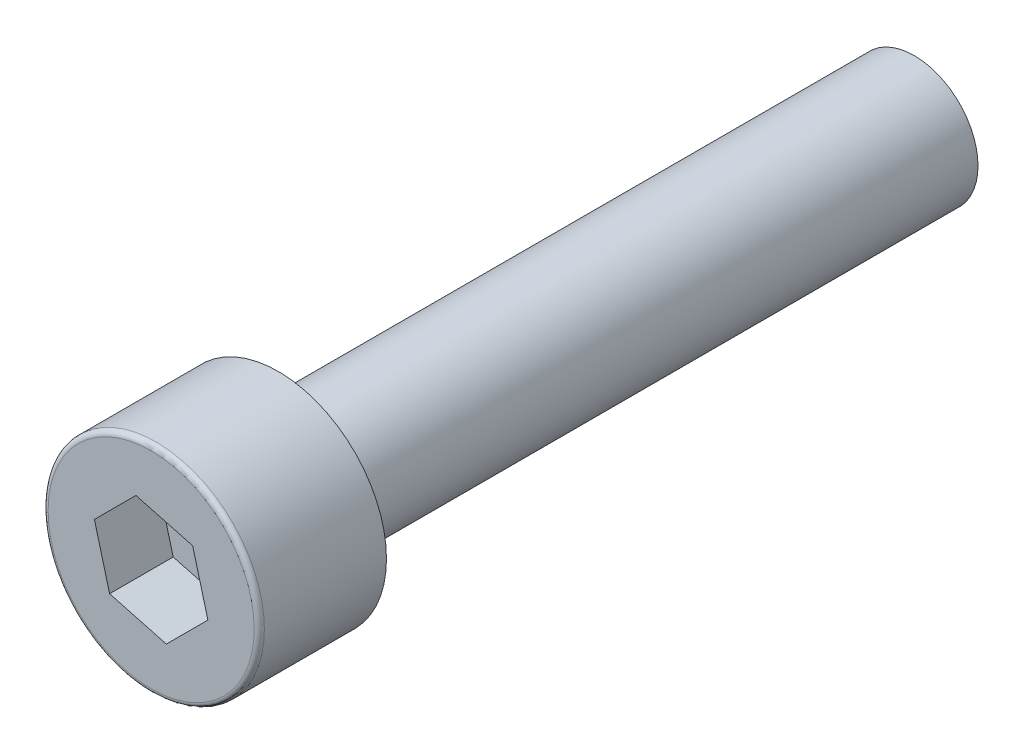
SolidWorks part; units mm, degrees
ref_plane "前视基准面" through (0, 0, 0) normal (0, 0, 1) x (1, 0, 0)
ref_plane "上视基准面" through (0, 0, 0) normal (0, 1, 0) x (1, 0, 0)
ref_plane "右视基准面" through (0, 0, 0) normal (1, 0, 0) x (0, 0, -1)
sketch "草图1" plane through (0, 0, 0) normal (0, 0, 1) x (1, 0, 0)
  circle A0 centre (0, 0) radius 4.25
  dimension "D1" = 8.5
extrude "凸台-拉伸1" add sketch "草图1" along normal blind 5
sketch "草图2" plane through (0, 0, 5) normal (0, 0, 1) x (1, 0, 0)
  line L1 (-1.633, -1.633) -> (0.5977, -2.2307)
  line L2 (0.5977, -2.2307) -> (2.2307, -0.5977)
  line L3 (2.2307, -0.5977) -> (1.633, 1.633)
  line L4 (1.633, 1.633) -> (-0.5977, 2.2307)
  line L5 (-0.5977, 2.2307) -> (-2.2307, 0.5977)
  line L6 (-2.2307, 0.5977) -> (-1.633, -1.633)
  circle A0 centre (0, 0) radius 2 construction
  dimension "D1" = 4
extrude "切除-拉伸1" cut sketch "草图2" against normal blind 2.5
sketch "草图3" plane through (0, 0, 0) normal (0, 0, -1) x (-1, 0, 0)
  circle A0 centre (0, 0) radius 2.5
  dimension "D1" = 5
extrude "凸台-拉伸2" add sketch "草图3" along normal blind 25
fillet "圆角1" radius 0.2 1 edges at (4.25, 0, 5)
